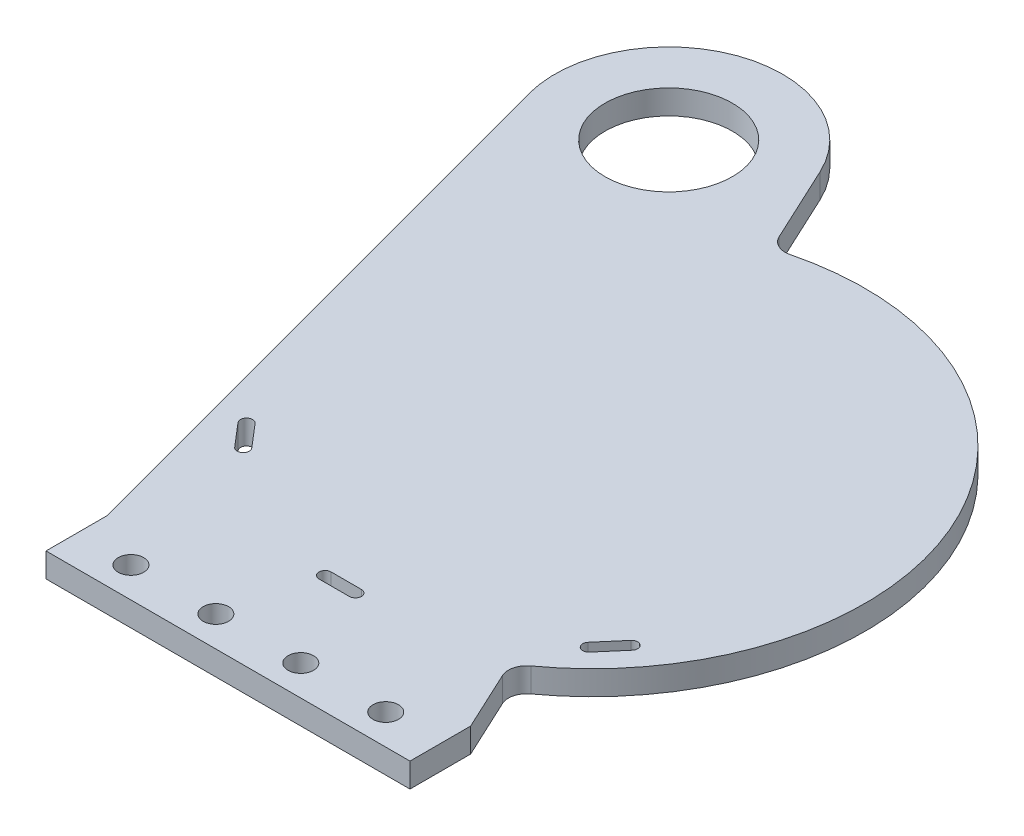
SolidWorks part; units mm, degrees
ref_plane "前视基准面" through (0, 0, 0) normal (0, 0, 1) x (1, 0, 0)
ref_plane "上视基准面" through (0, 0, 0) normal (0, 1, 0) x (1, 0, 0)
ref_plane "右视基准面" through (0, 0, 0) normal (1, 0, 0) x (0, 0, -1)
sketch "草图1" plane through (0, 0, 0) normal (0, 1, 0) x (1, 0, 0)
  line L0 (-113.4694, 0) -> (114.6939, 0) construction
  line L1 (0, 62.8571) -> (0, -63.6735) construction
  line L2 (0, 0) -> (60, 0)
  line L3 (60, 0) -> (60, 10)
  line L4 (0, 0) -> (0, 10)
  line L5 (0, 10) -> (-81.05, 312.4827) construction
  line L6 (-81.05, 312.4827) -> (60, 10) construction
  line L7 (0, 10) -> (-25.4925, 105.1394)
  line L8 (9.6682, 117.9368) -> (15.5695, 105.2815)
  line L9 (-27.7778, 5) -> (109.3349, 5) construction
  line L10 (30, 63.3089) -> (30, -22.2801) construction
  line L11 (55.4119, 19.8392) -> (60, 10)
  line L12 (26.5, 19.5) -> (31.5, 19.5) construction
  line L13 (26.5, 20.5) -> (31.5, 20.5)
  line L14 (26.5, 18.5) -> (31.5, 18.5)
  line L15 (-1.7353, 34.7934) -> (1.5173, 30.9959) construction
  line L16 (-0.9758, 35.4439) -> (2.2768, 31.6464)
  line L17 (-2.4948, 34.1429) -> (0.7578, 30.3454)
  line L18 (30, 60) -> (0, 34.3047) construction
  line L19 (61.7353, 34.7934) -> (58.4827, 30.9959) construction
  line L20 (60.9758, 35.4439) -> (57.7232, 31.6464)
  line L21 (62.4948, 34.1429) -> (59.2422, 30.3454)
  arc A0 (-25.4925, 105.1394) -> (9.6682, 117.9368) centre (-7.3523, 110) cw
  circle A1 centre (-7.3523, 110) radius 10.5
  circle A2 centre (30, 60) radius 39.5 construction
  circle A3 centre (30, 60) radius 41.5 construction
  arc A4 (19.0204, 103.64) -> (56.3726, 23.5379) centre (30, 60) cw
  arc A5 (55.4119, 19.8392) -> (56.3726, 23.5379) centre (58.1308, 21.1071) cw
  arc A6 (15.5695, 105.2815) -> (19.0204, 103.64) centre (18.2884, 106.5493) ccw
  arc A7 (26.5, 20.5) -> (26.5, 18.5) centre (26.5, 19.5) ccw
  arc A8 (31.5, 18.5) -> (31.5, 20.5) centre (31.5, 19.5) ccw
  arc A9 (-0.9758, 35.4439) -> (-2.4948, 34.1429) centre (-1.7353, 34.7934) ccw
  arc A10 (0.7578, 30.3454) -> (2.2768, 31.6464) centre (1.5173, 30.9959) ccw
  arc A11 (60.9758, 35.4439) -> (62.4948, 34.1429) centre (61.7353, 34.7934) cw
  arc A12 (59.2422, 30.3454) -> (57.7232, 31.6464) centre (58.4827, 30.9959) cw
  point P13 (30, 0)
  point P19 (0, 5)
  point P31 (29, 19.5)
  point P36 (-0.109, 32.8947)
  point P41 (0, 0)
  point P47 (60.109, 32.8947)
  dimension "D6" = 110
  dimension "D7" = 18.7801
  dimension "D8" = 21
  dimension "D10" = 60
  dimension "D11" = 83
  dimension "D9" = 45
  dimension "D12" = 79
  dimension "D13" = 3
  dimension "D15" = 1
  dimension "D18" = 1
  dimension "D1" = 60
  dimension "D2" = 10
  dimension "D3" = 10
  dimension "D4" = 15
  dimension "D5" = 25
  dimension "D14" = 5
  dimension "D16" = 1
  dimension "D17" = 5
  dimension "D19" = 1
extrude "凸台-拉伸1" add sketch "草图1" along normal blind 4
sketch "草图4" plane through (0, 0, 0) normal (0, -1, 0) x (1, 0, 0)
  line L0 (-27.1286, -5) -> (89.0413, -5) construction
  line L1 (30, 9.6103) -> (30, -9.0276) construction
  line L2 (0, 0) -> (60, 0) construction
  line L3 (0, -10) -> (0, 0) construction
  circle A0 centre (37, -5) radius 2.1
  circle A1 centre (51, -5) radius 2.1
  circle A2 centre (9, -5) radius 2.1
  circle A3 centre (23, -5) radius 2.1
  point P7 (30, 0)
  point P11 (0, -5)
  dimension "D1" = 7
  dimension "D3" = 4.2
  dimension "D4" = 4.2
  dimension "D2" = 14
extrude "设计平台安装孔" cut sketch "草图4" against normal through all
